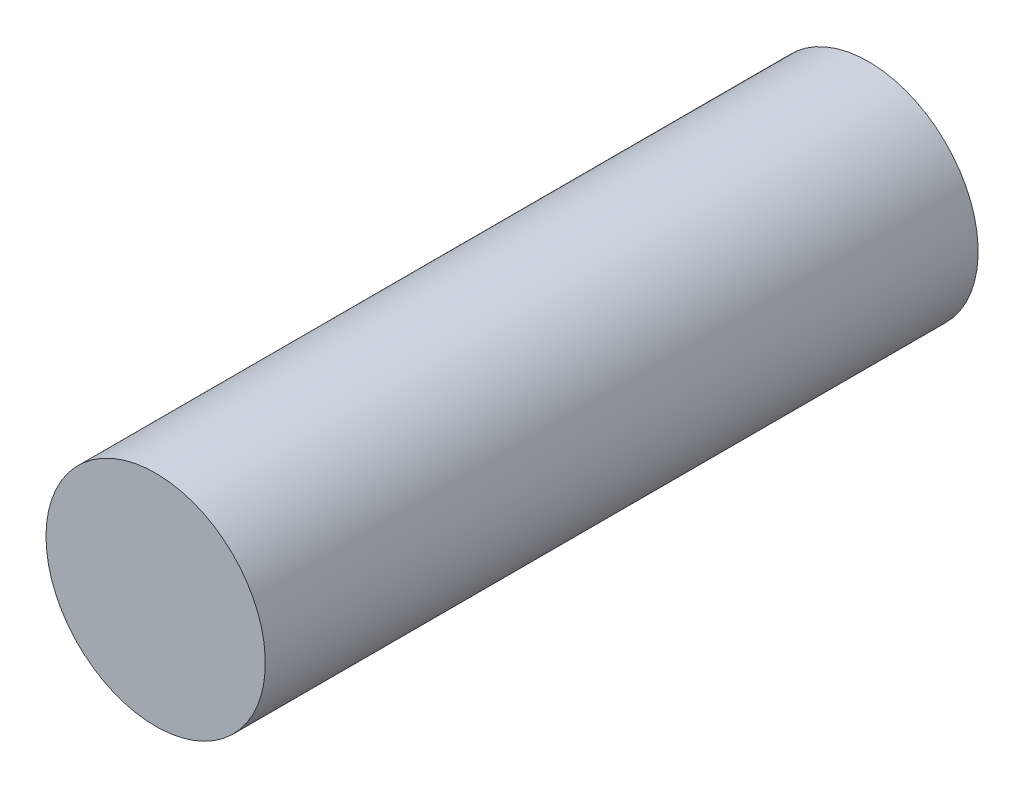
SolidWorks part; units mm, degrees
ref_plane "Front Plane" through (0, 0, 0) normal (0, 0, 1) x (1, 0, 0)
ref_plane "Top Plane" through (0, 0, 0) normal (0, 1, 0) x (1, 0, 0)
ref_plane "Right Plane" through (0, 0, 0) normal (1, 0, 0) x (0, 0, -1)
sketch "Sketch1" plane through (0, 0, 0) normal (0, 0, 1) x (1, 0, 0)
  circle A0 centre (0, 0) radius 2
extrude "Boss-Extrude1" add sketch "Sketch1" along normal blind 13
